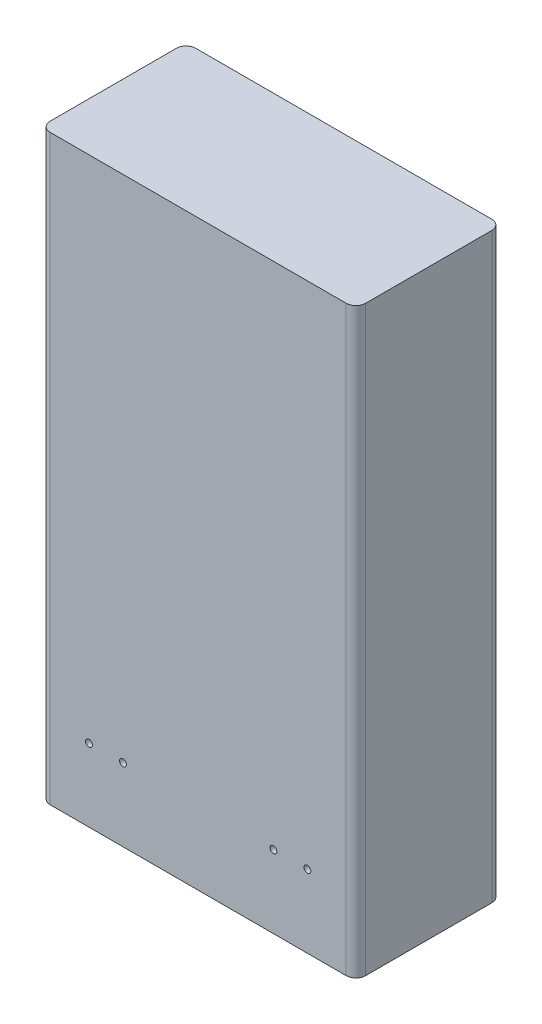
SolidWorks part; units mm, degrees
material "Mahogany"
ref_plane "Front Plane" through (0, 0, 0) normal (0, 0, 1) x (1, 0, 0)
ref_plane "Top Plane" through (0, 0, 0) normal (0, 1, 0) x (1, 0, 0)
ref_plane "Right Plane" through (0, 0, 0) normal (1, 0, 0) x (0, 0, -1)
sketch "Sketch1" plane through (0, 0, 0) normal (0, 0, 1) x (1, 0, 0)
  line L1 (-41.275, -76.2) -> (41.275, -76.2)
  line L2 (-41.275, -76.2) -> (-41.275, 76.2)
  line L3 (-41.275, 76.2) -> (41.275, 76.2)
  line L4 (41.275, -76.2) -> (41.275, 76.2)
  line L5 (-41.275, -76.2) -> (41.275, 76.2) construction
  line L6 (-41.275, 76.2) -> (41.275, -76.2) construction
  point P0 (0, 0)
  dimension "D1" = 152.4
  dimension "D2" = 82.55
extrude "Boss-Extrude1" add sketch "Sketch1" along normal mid plane 38.1
sketch "Sketch2" plane through (0, 0, 19.05) normal (0, 0, 1) x (1, 0, 0)
  line L0 (41.275, -76.2) -> (41.275, 76.2) construction
  line L1 (-28.575, 57.15) -> (28.575, 57.15) construction
  line L2 (-28.575, 57.15) -> (-28.575, -57.15) construction
  line L3 (-28.575, -57.15) -> (28.575, -57.15) construction
  line L4 (28.575, 57.15) -> (28.575, -57.15) construction
  line L5 (-28.575, 57.15) -> (28.575, -57.15) construction
  line L6 (-28.575, -57.15) -> (28.575, 57.15) construction
  line L7 (-41.275, -76.2) -> (41.275, -76.2) construction
  circle A0 centre (-28.575, -57.15) radius 0.889
  circle A1 centre (-19.685, -57.15) radius 0.889
  circle A2 centre (28.575, -57.15) radius 0.889
  circle A3 centre (19.685, -57.15) radius 0.889
  point P0 (0, 0)
  dimension "D3" = 1.778
  dimension "D1" = 12.7
  dimension "D2" = 19.05
  dimension "D4" = 8.89
  dimension "D5" = 8.89
extrude "Cut-Extrude1" cut sketch "Sketch2" against normal through all
fillet "Fillet1" radius 2.54 4 edges at (41.275, 0, -19.05) (41.275, 0, 19.05) (-41.275, 0, -19.05) (-41.275, 0, 19.05)
equation "\"D5@Sketch2\"=\"D4@Sketch2\""
